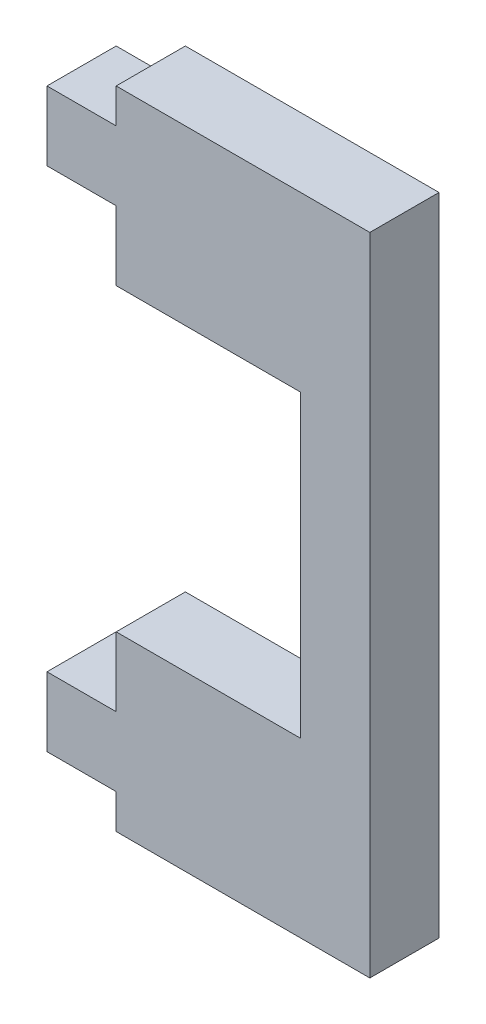
SolidWorks part; units mm, degrees
ref_plane "Alzado" through (0, 0, 0) normal (0, 0, 1) x (1, 0, 0)
ref_plane "Planta" through (0, 0, 0) normal (0, 1, 0) x (1, 0, 0)
ref_plane "Vista lateral" through (0, 0, 0) normal (1, 0, 0) x (0, 0, -1)
sketch "Croquis1" plane through (0, 0, 0) normal (0, 0, 1) x (1, 0, 0)
  line L3 (-8, 12.5) -> (-11, 12.5)
  line L4 (-11, 12.5) -> (-11, 9.5)
  line L7 (-8, 12.5) -> (-8, 14)
  line L8 (-8, 14) -> (3, 14)
  line L15 (-8, 6.5) -> (-8, 9.5)
  line L16 (-8, 9.5) -> (-11, 9.5)
  line L17 (-8, 6.5) -> (0, 6.5)
  line L18 (0, 6.5) -> (0, 0)
  line L19 (3, 14) -> (3, 0)
  line L20 (0, 0) -> (3, 0)
  point P15 (3, 0)
  dimension "D1" = 6.5
  dimension "D2" = 3
  dimension "D3" = 1.5
  dimension "D4" = 14
extrude "Saliente-Extruir1" add sketch "Croquis1" along normal blind 3
mirror "Simetría1" about plane through (0, 0, 3) normal (0, 1, 0) of "Saliente-Extruir1"
